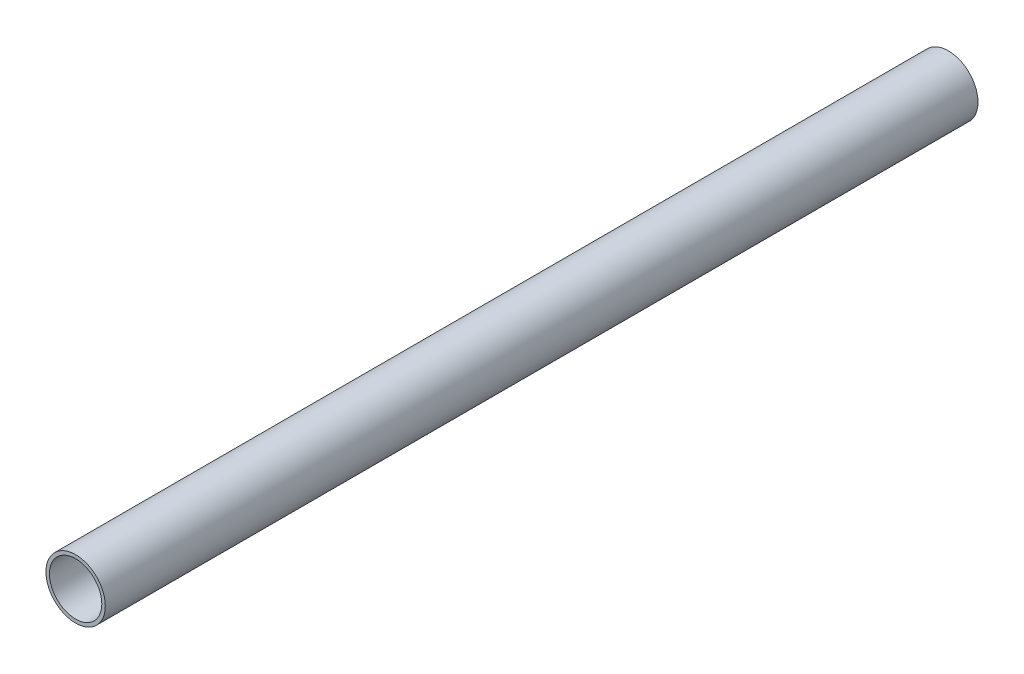
SolidWorks part; units mm, degrees
ref_plane "Front Plane" through (0, 0, 0) normal (0, 0, 1) x (1, 0, 0)
ref_plane "Top Plane" through (0, 0, 0) normal (0, 1, 0) x (1, 0, 0)
ref_plane "Right Plane" through (0, 0, 0) normal (1, 0, 0) x (0, 0, -1)
sketch "Sketch1" plane through (0, 0, 0) normal (0, 0, 1) x (1, 0, 0)
  circle A0 centre (0, 0) radius 15
  circle A1 centre (0, 0) radius 17
  dimension "D1" = 30
  dimension "D2" = 2
extrude "Boss-Extrude1" add sketch "Sketch1" along normal mid plane 500 contours A1 A0
